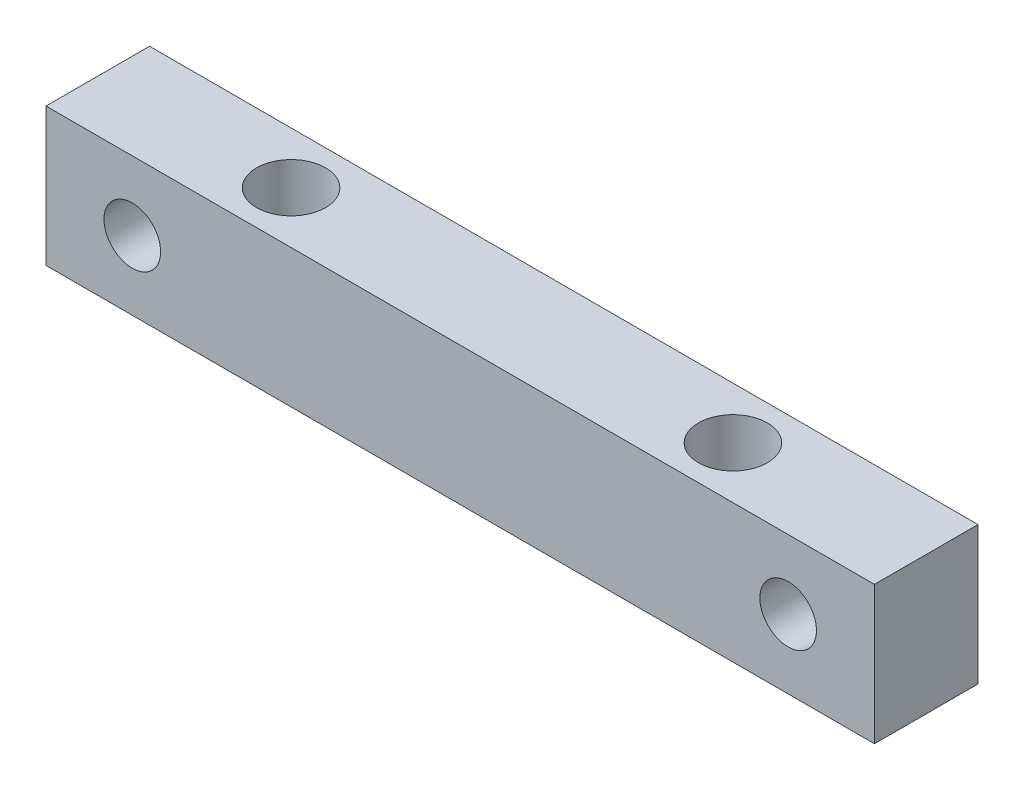
SolidWorks part; units mm, degrees
ref_plane "Front Plane" through (0, 0, 0) normal (0, 0, 1) x (1, 0, 0)
ref_plane "Top Plane" through (0, 0, 0) normal (0, 1, 0) x (1, 0, 0)
ref_plane "Right Plane" through (0, 0, 0) normal (1, 0, 0) x (0, 0, -1)
sketch "Sketch1" plane through (0, 788.1561, 0) normal (0, 1, 0) x (1, 0, 0)
  line L0 (38.1, -152.4) -> (38.1, 76.2) construction
  line L1 (-38.1, 63.5) -> (38.1, 63.5)
  line L2 (-38.1, 63.5) -> (-38.1, 53.975)
  line L3 (-38.1, 53.975) -> (38.1, 53.975)
  line L4 (38.1, 63.5) -> (38.1, 53.975)
  line L5 (-38.1, -152.4) -> (-38.1, 76.2) construction
  line L6 (0, 53.975) -> (0, 63.5) construction
  line L7 (-25.4, 63.5) -> (-25.4, 53.975) construction
  line L8 (-38.1, 58.7375) -> (0, 58.7375) construction
  line L10 (-38.1, 76.2) -> (38.1, 76.2) construction
  circle A0 centre (-20.32, 58.7375) radius 3.175
  circle A1 centre (20.32, 58.7375) radius 3.175
  point P20 (0, 0)
  dimension "D2" = 6.35
  dimension "D1" = 9.525
  dimension "D3" = 12.7
  dimension "D4" = 12.7
  dimension "D5" = 17.78
extrude "Boss-Extrude1" add sketch "Sketch1" along normal blind 12.7
sketch "Sketch2" plane through (0, 0, -63.5) normal (0, 0, -1) x (-1, 0, 0)
  circle A0 centre (30.1625, 794.5061) radius 3.175 construction
  circle A1 centre (-30.1625, 794.5061) radius 3.175 construction
  circle A2 centre (30.1625, 794.5061) radius 3.175 construction
  circle A3 centre (-30.1625, 794.5061) radius 3.175 construction
  circle A4 centre (30.1625, 794.5061) radius 2.6035
  circle A5 centre (-30.1625, 794.5061) radius 2.6035
  dimension "D1" = 5.207
extrude "Cut-Extrude1" cut sketch "Sketch2" against normal up to next
